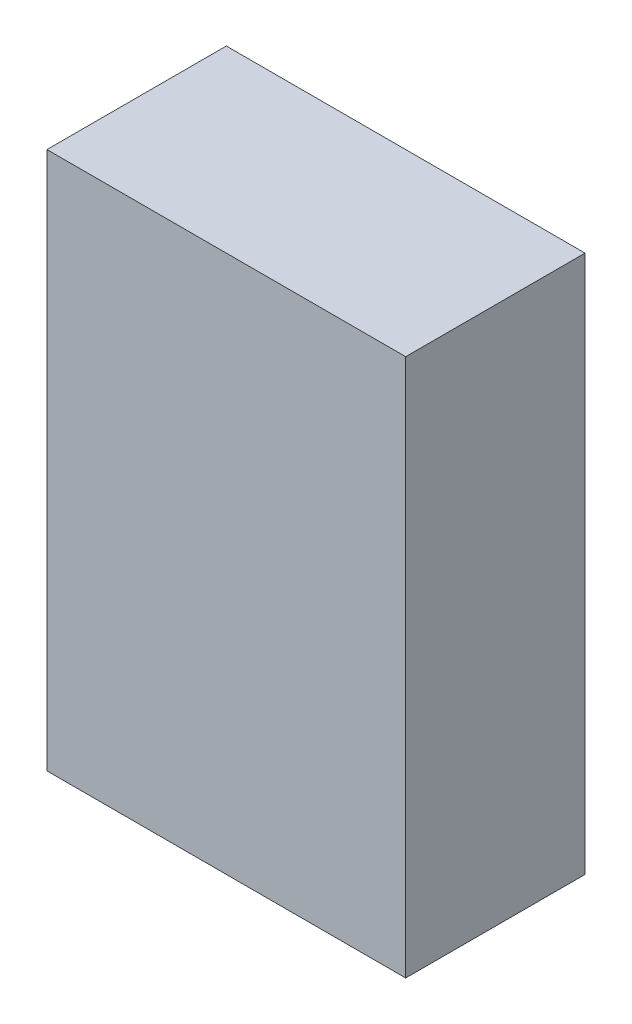
SolidWorks part; units mm, degrees
ref_plane "Front Plane" through (0, 0, 0) normal (0, 0, 1) x (1, 0, 0)
ref_plane "Top Plane" through (0, 0, 0) normal (0, 1, 0) x (1, 0, 0)
ref_plane "Right Plane" through (0, 0, 0) normal (1, 0, 0) x (0, 0, -1)
sketch "Sketch1" plane through (0, 0, 0) normal (0, 1, 0) x (1, 0, 0)
  line L1 (-25.4, -12.7) -> (25.4, -12.7)
  line L2 (-25.4, -12.7) -> (-25.4, 12.7)
  line L3 (-25.4, 12.7) -> (25.4, 12.7)
  line L4 (25.4, -12.7) -> (25.4, 12.7)
  line L5 (-25.4, -12.7) -> (25.4, 12.7) construction
  line L6 (-25.4, 12.7) -> (25.4, -12.7) construction
  point P0 (0, 0)
  dimension "D1" = 50.8
  dimension "D2" = 25.4
extrude "Demo-Extrude" add sketch "Sketch1" along normal blind 76.2
